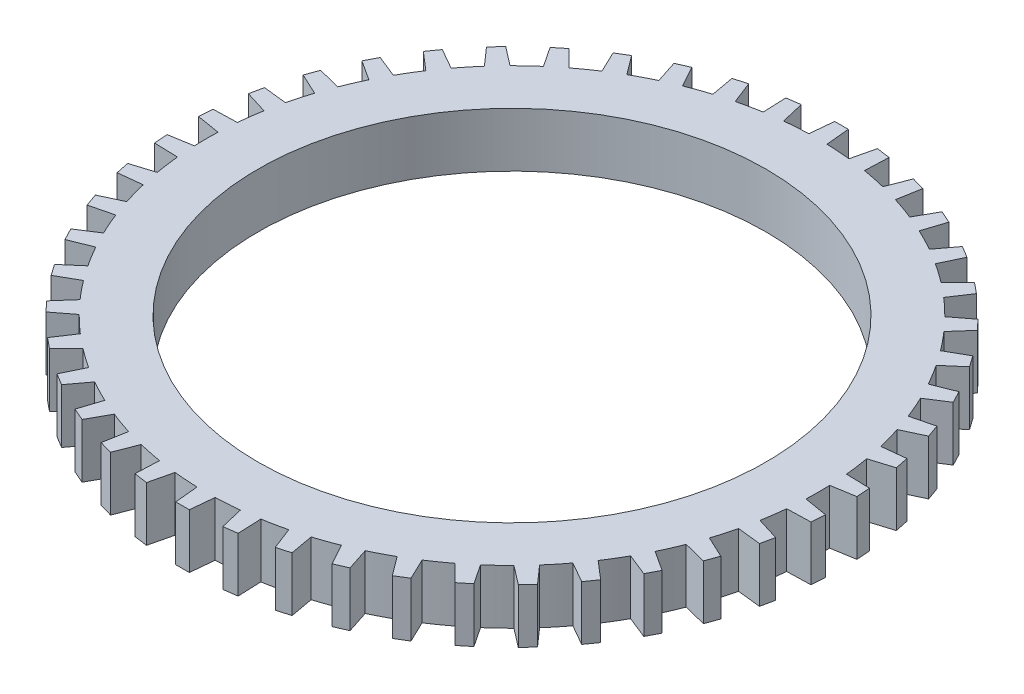
SolidWorks part; units mm, degrees
ref_plane "Alzado" through (0, 0, 0) normal (0, 0, 1) x (1, 0, 0)
ref_plane "Planta" through (0, 0, 0) normal (0, 1, 0) x (1, 0, 0)
ref_plane "Vista lateral" through (0, 0, 0) normal (1, 0, 0) x (0, 0, -1)
sketch "Croquis1" plane through (0, 0, 0) normal (0, 1, 0) x (1, 0, 0)
  line L0 (-0.5, 16.8684) -> (-0.375, 18.1684)
  line L1 (-0.375, 18.1684) -> (0.375, 18.1684)
  line L2 (0.375, 18.1684) -> (0.5, 16.8684)
  line L3 (0, 7.8235) -> (0, -7.8675) construction
  line L4 (1.8016, 16.7793) -> (2.1024, 18.0502)
  line L5 (2.1024, 18.0502) -> (2.8454, 17.9481)
  line L6 (2.8454, 17.9481) -> (2.7923, 16.6432)
  line L7 (4.0696, 16.3777) -> (4.5407, 17.5958)
  line L8 (4.5407, 17.5958) -> (5.2629, 17.3935)
  line L9 (5.2629, 17.3935) -> (5.0325, 16.1079)
  line L10 (6.2618, 15.671) -> (6.8943, 16.8136)
  line L11 (6.8943, 16.8136) -> (7.5822, 16.5148)
  line L12 (7.5822, 16.5148) -> (7.179, 15.2726)
  line L13 (8.3373, 14.6724) -> (9.1196, 15.7182)
  line L14 (9.1196, 15.7182) -> (9.7604, 15.3286)
  line L15 (9.7604, 15.3286) -> (9.1917, 14.1529)
  line L16 (10.2576, 13.4005) -> (11.1749, 14.3301)
  line L17 (11.1749, 14.3301) -> (11.7567, 13.8567)
  line L18 (11.7567, 13.8567) -> (11.0333, 12.7694)
  line L19 (11.9867, 11.879) -> (13.0221, 12.6749)
  line L20 (13.0221, 12.6749) -> (13.534, 12.1268)
  line L21 (13.534, 12.1268) -> (12.6693, 11.1481)
  line L22 (13.4926, 10.1361) -> (14.6267, 10.7837)
  line L23 (14.6267, 10.7837) -> (15.0593, 10.171)
  line L24 (15.0593, 10.171) -> (14.0693, 9.3192)
  line L25 (14.7471, 8.2045) -> (15.9589, 8.6916)
  line L26 (15.9589, 8.6916) -> (16.3039, 8.0257)
  line L27 (16.3039, 8.0257) -> (15.2072, 7.3166)
  line L28 (15.727, 6.12) -> (16.9938, 6.4376)
  line L29 (16.9938, 6.4376) -> (17.2449, 5.7309)
  line L30 (17.2449, 5.7309) -> (16.0618, 5.1777)
  line L31 (16.4138, 3.9215) -> (17.7121, 4.0636)
  line L32 (17.7121, 4.0636) -> (17.8646, 3.3293)
  line L33 (17.8646, 3.3293) -> (16.6173, 2.9424)
  line L34 (16.7949, 1.65) -> (18.1004, 1.614)
  line L35 (18.1004, 1.614) -> (18.1516, 0.8657)
  line L36 (18.1516, 0.8657) -> (16.8632, 0.6523)
  line L37 (16.8632, -0.6523) -> (18.1516, -0.8657)
  line L38 (18.1516, -0.8657) -> (18.1004, -1.614)
  line L39 (18.1004, -1.614) -> (16.7949, -1.65)
  line L40 (16.6173, -2.9424) -> (17.8646, -3.3293)
  line L41 (17.8646, -3.3293) -> (17.7121, -4.0636)
  line L42 (17.7121, -4.0636) -> (16.4138, -3.9215)
  line L43 (16.0618, -5.1777) -> (17.2449, -5.7309)
  line L44 (17.2449, -5.7309) -> (16.9938, -6.4376)
  line L45 (16.9938, -6.4376) -> (15.727, -6.12)
  line L46 (15.2072, -7.3166) -> (16.3039, -8.0257)
  line L47 (16.3039, -8.0257) -> (15.9589, -8.6916)
  line L48 (15.9589, -8.6916) -> (14.7471, -8.2045)
  line L49 (14.0693, -9.3192) -> (15.0593, -10.171)
  line L50 (15.0593, -10.171) -> (14.6267, -10.7837)
  line L51 (14.6267, -10.7837) -> (13.4926, -10.1361)
  line L52 (12.6693, -11.1481) -> (13.534, -12.1268)
  line L53 (13.534, -12.1268) -> (13.0221, -12.6749)
  line L54 (13.0221, -12.6749) -> (11.9867, -11.879)
  line L55 (11.0333, -12.7694) -> (11.7567, -13.8567)
  line L56 (11.7567, -13.8567) -> (11.1749, -14.3301)
  line L57 (11.1749, -14.3301) -> (10.2576, -13.4005)
  line L58 (9.1917, -14.1529) -> (9.7604, -15.3286)
  line L59 (9.7604, -15.3286) -> (9.1196, -15.7182)
  line L60 (9.1196, -15.7182) -> (8.3373, -14.6724)
  line L61 (7.179, -15.2726) -> (7.5822, -16.5148)
  line L62 (7.5822, -16.5148) -> (6.8943, -16.8136)
  line L63 (6.8943, -16.8136) -> (6.2618, -15.671)
  line L64 (5.0325, -16.1079) -> (5.2629, -17.3935)
  line L65 (5.2629, -17.3935) -> (4.5407, -17.5958)
  line L66 (4.5407, -17.5958) -> (4.0696, -16.3777)
  line L67 (2.7923, -16.6432) -> (2.8454, -17.9481)
  line L68 (2.8454, -17.9481) -> (2.1024, -18.0502)
  line L69 (2.1024, -18.0502) -> (1.8016, -16.7793)
  line L70 (0.5, -16.8684) -> (0.375, -18.1684)
  line L71 (0.375, -18.1684) -> (-0.375, -18.1684)
  line L72 (-0.375, -18.1684) -> (-0.5, -16.8684)
  line L73 (-1.8016, -16.7793) -> (-2.1024, -18.0502)
  line L74 (-2.1024, -18.0502) -> (-2.8454, -17.9481)
  line L75 (-2.8454, -17.9481) -> (-2.7923, -16.6432)
  line L76 (-4.0696, -16.3777) -> (-4.5407, -17.5958)
  line L77 (-4.5407, -17.5958) -> (-5.2629, -17.3935)
  line L78 (-5.2629, -17.3935) -> (-5.0325, -16.1079)
  line L79 (-6.2618, -15.671) -> (-6.8943, -16.8136)
  line L80 (-6.8943, -16.8136) -> (-7.5822, -16.5148)
  line L81 (-7.5822, -16.5148) -> (-7.179, -15.2726)
  line L82 (-8.3373, -14.6724) -> (-9.1196, -15.7182)
  line L83 (-9.1196, -15.7182) -> (-9.7604, -15.3286)
  line L84 (-9.7604, -15.3286) -> (-9.1917, -14.1529)
  line L85 (-10.2576, -13.4005) -> (-11.1749, -14.3301)
  line L86 (-11.1749, -14.3301) -> (-11.7567, -13.8567)
  line L87 (-11.7567, -13.8567) -> (-11.0333, -12.7694)
  line L88 (-11.9867, -11.879) -> (-13.0221, -12.6749)
  line L89 (-13.0221, -12.6749) -> (-13.534, -12.1268)
  line L90 (-13.534, -12.1268) -> (-12.6693, -11.1481)
  line L91 (-13.4926, -10.1361) -> (-14.6267, -10.7837)
  line L92 (-14.6267, -10.7837) -> (-15.0593, -10.171)
  line L93 (-15.0593, -10.171) -> (-14.0693, -9.3192)
  line L94 (-14.7471, -8.2045) -> (-15.9589, -8.6916)
  line L95 (-15.9589, -8.6916) -> (-16.3039, -8.0257)
  line L96 (-16.3039, -8.0257) -> (-15.2072, -7.3166)
  line L97 (-15.727, -6.12) -> (-16.9938, -6.4376)
  line L98 (-16.9938, -6.4376) -> (-17.2449, -5.7309)
  line L99 (-17.2449, -5.7309) -> (-16.0618, -5.1777)
  line L100 (-16.4138, -3.9215) -> (-17.7121, -4.0636)
  line L101 (-17.7121, -4.0636) -> (-17.8646, -3.3293)
  line L102 (-17.8646, -3.3293) -> (-16.6173, -2.9424)
  line L103 (-16.7949, -1.65) -> (-18.1004, -1.614)
  line L104 (-18.1004, -1.614) -> (-18.1516, -0.8657)
  line L105 (-18.1516, -0.8657) -> (-16.8632, -0.6523)
  line L106 (-16.8632, 0.6523) -> (-18.1516, 0.8657)
  line L107 (-18.1516, 0.8657) -> (-18.1004, 1.614)
  line L108 (-18.1004, 1.614) -> (-16.7949, 1.65)
  line L109 (-16.6173, 2.9424) -> (-17.8646, 3.3293)
  line L110 (-17.8646, 3.3293) -> (-17.7121, 4.0636)
  line L111 (-17.7121, 4.0636) -> (-16.4138, 3.9215)
  line L112 (-16.0618, 5.1777) -> (-17.2449, 5.7309)
  line L113 (-17.2449, 5.7309) -> (-16.9938, 6.4376)
  line L114 (-16.9938, 6.4376) -> (-15.727, 6.12)
  line L115 (-15.2072, 7.3166) -> (-16.3039, 8.0257)
  line L116 (-16.3039, 8.0257) -> (-15.9589, 8.6916)
  line L117 (-15.9589, 8.6916) -> (-14.7471, 8.2045)
  line L118 (-14.0693, 9.3192) -> (-15.0593, 10.171)
  line L119 (-15.0593, 10.171) -> (-14.6267, 10.7837)
  line L120 (-14.6267, 10.7837) -> (-13.4926, 10.1361)
  line L121 (-12.6693, 11.1481) -> (-13.534, 12.1268)
  line L122 (-13.534, 12.1268) -> (-13.0221, 12.6749)
  line L123 (-13.0221, 12.6749) -> (-11.9867, 11.879)
  line L124 (-11.0333, 12.7694) -> (-11.7567, 13.8567)
  line L125 (-11.7567, 13.8567) -> (-11.1749, 14.3301)
  line L126 (-11.1749, 14.3301) -> (-10.2576, 13.4005)
  line L127 (-9.1917, 14.1529) -> (-9.7604, 15.3286)
  line L128 (-9.7604, 15.3286) -> (-9.1196, 15.7182)
  line L129 (-9.1196, 15.7182) -> (-8.3373, 14.6724)
  line L130 (-7.179, 15.2726) -> (-7.5822, 16.5148)
  line L131 (-7.5822, 16.5148) -> (-6.8943, 16.8136)
  line L132 (-6.8943, 16.8136) -> (-6.2618, 15.671)
  line L133 (-5.0325, 16.1079) -> (-5.2629, 17.3935)
  line L134 (-5.2629, 17.3935) -> (-4.5407, 17.5958)
  line L135 (-4.5407, 17.5958) -> (-4.0696, 16.3777)
  line L136 (-2.7923, 16.6432) -> (-2.8454, 17.9481)
  line L137 (-2.8454, 17.9481) -> (-2.1024, 18.0502)
  line L138 (-2.1024, 18.0502) -> (-1.8016, 16.7793)
  arc A0 (-5.0325, 16.1079) -> (-6.2618, 15.671) centre (0, 0) ccw
  circle A1 centre (0, 0) radius 14
  arc A2 (-7.179, 15.2726) -> (-8.3373, 14.6724) centre (0, 0) ccw
  arc A3 (-9.1917, 14.1529) -> (-10.2576, 13.4005) centre (0, 0) ccw
  arc A4 (-11.0333, 12.7694) -> (-11.9867, 11.879) centre (0, 0) ccw
  arc A5 (-2.7923, 16.6432) -> (-4.0696, 16.3777) centre (0, 0) ccw
  arc A6 (-0.5, 16.8684) -> (-1.8016, 16.7793) centre (0, 0) ccw
  arc A7 (16.8632, -0.6523) -> (16.8632, 0.6523) centre (0, 0) ccw
  arc A8 (16.7949, 1.65) -> (16.6173, 2.9424) centre (0, 0) ccw
  arc A9 (16.4138, 3.9215) -> (16.0618, 5.1777) centre (0, 0) ccw
  arc A10 (15.727, 6.12) -> (15.2072, 7.3166) centre (0, 0) ccw
  arc A11 (14.7471, 8.2045) -> (14.0693, 9.3192) centre (0, 0) ccw
  arc A12 (16.6173, -2.9424) -> (16.7949, -1.65) centre (0, 0) ccw
  arc A13 (16.0618, -5.1777) -> (16.4138, -3.9215) centre (0, 0) ccw
  arc A14 (15.2072, -7.3166) -> (15.727, -6.12) centre (0, 0) ccw
  arc A15 (11.0333, -12.7694) -> (11.9867, -11.879) centre (0, 0) ccw
  arc A16 (12.6693, -11.1481) -> (13.4926, -10.1361) centre (0, 0) ccw
  arc A17 (14.0693, -9.3192) -> (14.7471, -8.2045) centre (0, 0) ccw
  arc A18 (7.179, -15.2726) -> (8.3373, -14.6724) centre (0, 0) ccw
  arc A19 (9.1917, -14.1529) -> (10.2576, -13.4005) centre (0, 0) ccw
  arc A20 (5.0325, -16.1079) -> (6.2618, -15.671) centre (0, 0) ccw
  arc A21 (2.7923, -16.6432) -> (4.0696, -16.3777) centre (0, 0) ccw
  arc A22 (0.5, -16.8684) -> (1.8016, -16.7793) centre (0, 0) ccw
  arc A23 (-1.8016, -16.7793) -> (-0.5, -16.8684) centre (0, 0) ccw
  arc A24 (-4.0696, -16.3777) -> (-2.7923, -16.6432) centre (0, 0) ccw
  arc A25 (-6.2618, -15.671) -> (-5.0325, -16.1079) centre (0, 0) ccw
  arc A26 (-8.3373, -14.6724) -> (-7.179, -15.2726) centre (0, 0) ccw
  arc A27 (-10.2576, -13.4005) -> (-9.1917, -14.1529) centre (0, 0) ccw
  arc A28 (-11.9867, -11.879) -> (-11.0333, -12.7694) centre (0, 0) ccw
  arc A29 (-13.4926, -10.1361) -> (-12.6693, -11.1481) centre (0, 0) ccw
  arc A30 (-14.7471, -8.2045) -> (-14.0693, -9.3192) centre (0, 0) ccw
  arc A31 (-15.727, -6.12) -> (-15.2072, -7.3166) centre (0, 0) ccw
  arc A32 (-16.4138, -3.9215) -> (-16.0618, -5.1777) centre (0, 0) ccw
  arc A33 (-16.7949, -1.65) -> (-16.6173, -2.9424) centre (0, 0) ccw
  arc A34 (-16.6173, 2.9424) -> (-16.7949, 1.65) centre (0, 0) ccw
  arc A35 (-16.8632, 0.6523) -> (-16.8632, -0.6523) centre (0, 0) ccw
  arc A36 (-16.0618, 5.1777) -> (-16.4138, 3.9215) centre (0, 0) ccw
  arc A37 (-15.2072, 7.3166) -> (-15.727, 6.12) centre (0, 0) ccw
  arc A38 (-14.0693, 9.3192) -> (-14.7471, 8.2045) centre (0, 0) ccw
  arc A39 (-12.6693, 11.1481) -> (-13.4926, 10.1361) centre (0, 0) ccw
  arc A40 (13.4926, 10.1361) -> (12.6693, 11.1481) centre (0, 0) ccw
  arc A41 (11.9867, 11.879) -> (11.0333, 12.7694) centre (0, 0) ccw
  arc A42 (10.2576, 13.4005) -> (9.1917, 14.1529) centre (0, 0) ccw
  arc A43 (8.3373, 14.6724) -> (7.179, 15.2726) centre (0, 0) ccw
  arc A44 (1.8016, 16.7793) -> (0.5, 16.8684) centre (0, 0) ccw
  arc A45 (4.0696, 16.3777) -> (2.7923, 16.6432) centre (0, 0) ccw
  arc A46 (6.2618, 15.671) -> (5.0325, 16.1079) centre (0, 0) ccw
  dimension "D5" = 28
  dimension "D1" = 1
  dimension "D2" = 0.75
  dimension "D3" = 1.3
  dimension "D4" = 46
extrude "Saliente-Extruir1" add sketch "Croquis1" along normal blind 3
